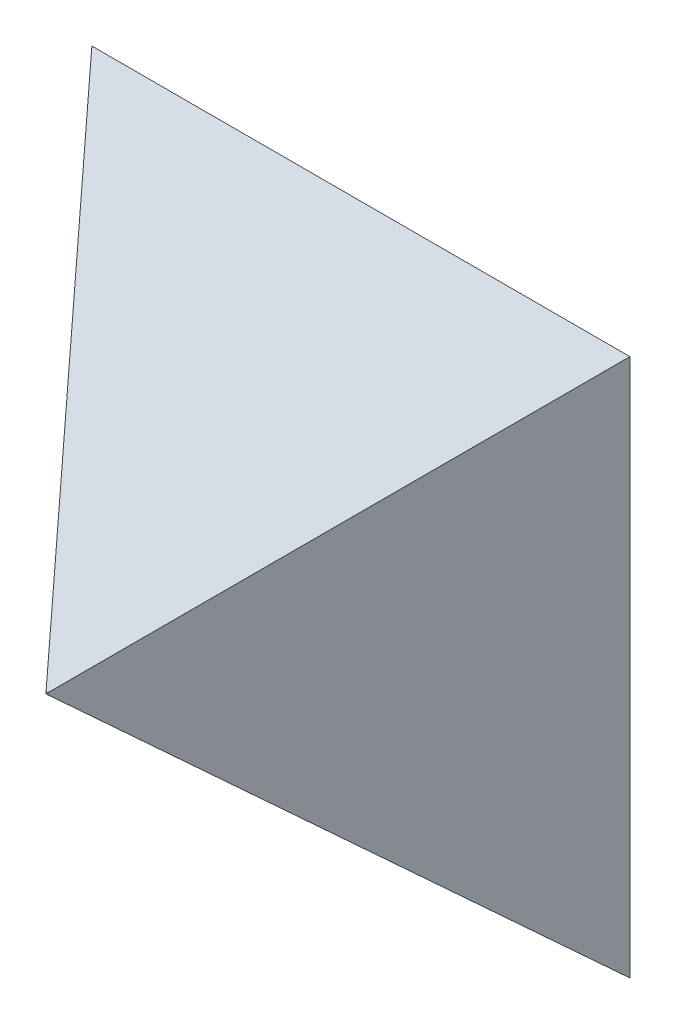
SolidWorks part; units mm, degrees
ref_plane "Plan de face" through (0, 0, 0) normal (0, 0, 1) x (1, 0, 0)
ref_plane "Plan de dessus" through (0, 0, 0) normal (0, 1, 0) x (1, 0, 0)
ref_plane "Plan de droite" through (0, 0, 0) normal (1, 0, 0) x (0, 0, -1)
sketch "Esquisse1" plane through (0, 0, 0) normal (0, 0, 1) x (1, 0, 0)
  line L1 (-12.7, -12.7) -> (12.7, -12.7)
  line L2 (-12.7, -12.7) -> (-12.7, 12.7)
  line L3 (-12.7, 12.7) -> (12.7, 12.7)
  line L4 (12.7, -12.7) -> (12.7, 12.7)
  line L5 (-12.7, -12.7) -> (12.7, 12.7) construction
  line L6 (-12.7, 12.7) -> (12.7, -12.7) construction
  point P0 (0, 0)
  dimension "D1" = 25.4
  dimension "D2" = 25.4
extrude "Boss.-Extru.1" add sketch "Esquisse1" along normal blind 14.8158 draft 40.5
ref_plane "Plan1" through (0, -12.7, 0) normal (0, 1, 0) x (1, 0, 0)
sketch "Esquisse2" plane through (0, -12.7, 0) normal (0, 1, 0) x (1, 0, 0)
  line L0 (0, 0) -> (0, -7.4079) construction
  line L1 (-12.7, 0) -> (12.7, 0) construction
  circle A0 centre (0, -7.4079) radius 1.6669
extrude "Enlèv. mat.-Extru.1" cut sketch "Esquisse2" along normal blind 12.7
